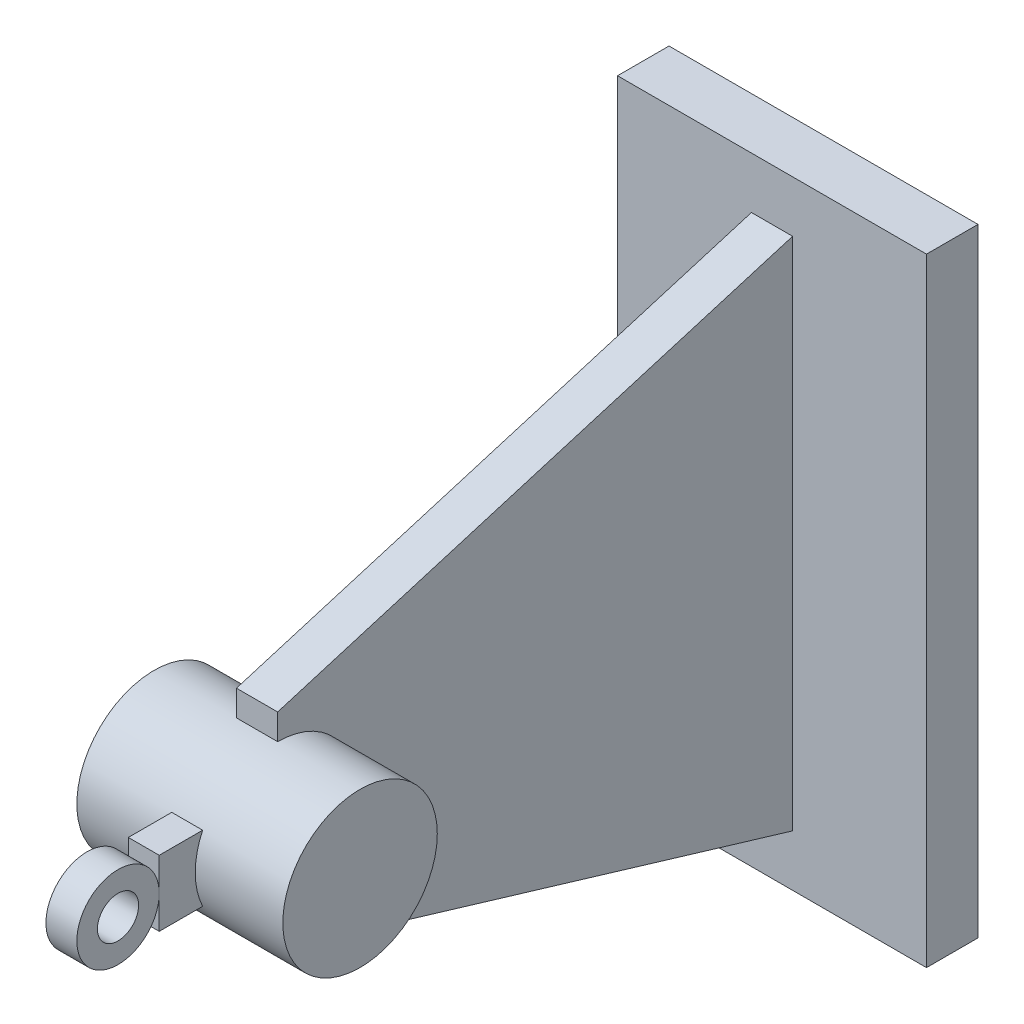
SolidWorks part; units mm, degrees
ref_plane "Front Plane" through (0, 0, 0) normal (1, 0, 0) x (0, 1, 0)
ref_plane "Top Plane" through (0, 0, 0) normal (0, 0, 1) x (0, 1, 0)
ref_plane "Right Plane" through (0, 0, 0) normal (0, 1, 0) x (-1, 0, 0)
sketch "Base Plate Sketch" plane through (0, 0, 0) normal (0, 0, 1) x (0, 1, 0)
  line L1 (-76.2, -38.1) -> (76.2, -38.1)
  line L2 (-76.2, -38.1) -> (-76.2, 38.1)
  line L3 (-76.2, 38.1) -> (76.2, 38.1)
  line L4 (76.2, -38.1) -> (76.2, 38.1)
  line L5 (-76.2, -38.1) -> (76.2, 38.1) construction
  line L6 (-76.2, 38.1) -> (76.2, -38.1) construction
  point P0 (0, 0)
extrude "Base Plate" add sketch "Base Plate Sketch" against normal blind 12.7
sketch "A-Frame Sketch" plane through (0, 0, 0) normal (1, 0, 0) x (0, 1, 0)
  line L0 (-63.5, 0) -> (63.5, 0)
  line L1 (63.5, 0) -> (25.4, 127)
  line L2 (25.4, 127) -> (-25.4, 127)
  line L3 (-25.4, 127) -> (-63.5, 0)
extrude "A-Frame Body" add sketch "A-Frame Sketch" along normal blind 5.08 and the other way blind 5.08
sketch "Center Cutout Sketch" plane through (0, 0, 0) normal (1, 0, 0) x (0, 1, 0)
  line L0 (-35.56, 25.4) -> (35.56, 25.4)
  line L1 (35.56, 25.4) -> (10.16, 88.9)
  line L2 (10.16, 88.9) -> (-10.16, 88.9)
  line L3 (-10.16, 88.9) -> (-35.56, 25.4)
sketch "Mounting Holes Sketch" plane through (0, 0, 0) normal (0, 0, 1) x (0, 1, 0)
  circle A0 centre (63.5, 25.4) radius 6.35
  circle A1 centre (-63.5, 25.4) radius 6.35
  circle A2 centre (63.5, -25.4) radius 6.35
  circle A3 centre (-63.5, -25.4) radius 6.35
sketch "Bearing Housing Sketch" plane through (0, 0, 0) normal (1, 0, 0) x (0, 1, 0)
  circle A0 centre (0, 127) radius 19.05
extrude "Bearing Housing" add sketch "Bearing Housing Sketch" along normal blind 25.4 and the other way blind 25.4
sketch "Bearing Hole Sketch" plane through (0, 0, 0) normal (1, 0, 0) x (0, 1, 0)
  circle A0 centre (0, 127) radius 9.525
sketch "Lifting Eyelet Sketch" plane through (0, 0, 0) normal (1, 0, 0) x (0, 1, 0)
  circle A0 centre (0, 165.1) radius 10.16
  circle A1 centre (0, 165.1) radius 5.08
extrude "Lifting Eyelet" add sketch "Lifting Eyelet Sketch" along normal blind 3.81 and the other way blind 3.81
sketch "Eyelet Connector Sketch" plane through (0, 0, 0) normal (1, 0, 0) x (0, 1, 0)
  line L1 (-8.128, 137.16) -> (8.128, 137.16)
  line L2 (-8.128, 137.16) -> (-8.128, 154.94)
  line L3 (-8.128, 154.94) -> (8.128, 154.94)
  line L4 (8.128, 137.16) -> (8.128, 154.94)
  line L5 (-8.128, 137.16) -> (8.128, 154.94) construction
  line L6 (-8.128, 154.94) -> (8.128, 137.16) construction
  circle A0 centre (0, 127) radius 19.05 construction
  point P0 (0, 146.05)
extrude "Eyelet Connector" add sketch "Eyelet Connector Sketch" along normal blind 3.81 and the other way blind 3.81
